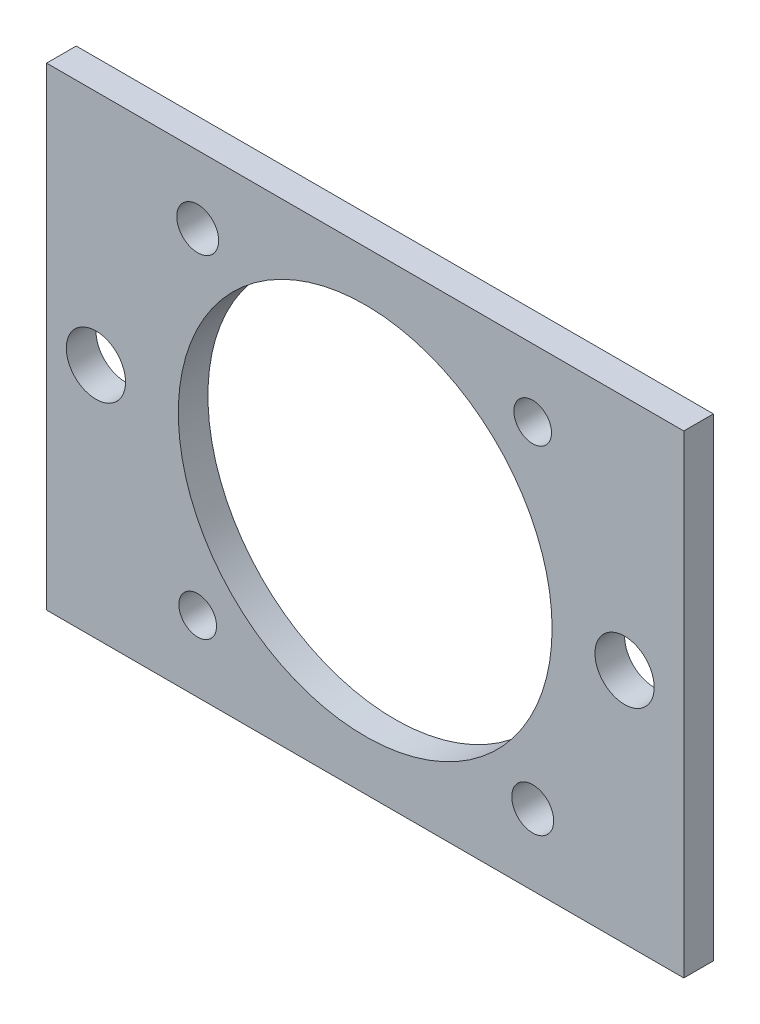
SolidWorks part; units mm, degrees
ref_plane "Front Plane" through (0, 0, 0) normal (0, 0, 1) x (1, 0, 0)
ref_plane "Top Plane" through (0, 0, 0) normal (0, 1, 0) x (1, 0, 0)
ref_plane "Right Plane" through (0, 0, 0) normal (1, 0, 0) x (0, 0, -1)
sketch "Sketch2" plane through (0, 0, 0) normal (0, 0, 1) x (1, 0, 0)
  line L0 (-34.163, -3.5154) -> (-28.8748, 0) construction
  line L1 (-34.163, -25.4) -> (34.163, -25.4)
  line L2 (-34.163, -25.4) -> (-34.163, 25.4)
  line L3 (-34.163, 25.4) -> (34.163, 25.4)
  line L4 (34.163, -25.4) -> (34.163, 25.4)
  line L5 (-28.8748, 0) -> (0, 0) construction
  line L6 (0, 0) -> (27.813, 0) construction
  line L7 (-17.9605, -17.7878) -> (17.9605, -17.7878) construction
  line L8 (-17.9605, -17.7878) -> (-17.9605, 18.1332) construction
  line L9 (-17.9605, 18.1332) -> (17.9605, 18.1332) construction
  line L10 (17.9605, -17.7878) -> (17.9605, 18.1332) construction
  line L11 (-17.9605, -17.7878) -> (17.9605, 18.1332) construction
  line L12 (-17.9605, 18.1332) -> (17.9605, -17.7878) construction
  line L13 (27.813, 0) -> (34.163, 0) construction
  circle A0 centre (-17.9605, 18.1332) radius 2.2479
  circle A1 centre (17.9605, 18.1332) radius 2.0193
  circle A2 centre (17.9605, -17.7878) radius 2.2479
  circle A3 centre (-17.9605, -17.7878) radius 2.0193
  circle A4 centre (0, 0) radius 20.0406
  circle A5 centre (-28.8748, 0) radius 3.175
  circle A6 centre (27.813, 0) radius 3.175
  point P0 (0, 0)
  point P6 (0, 0.1727)
  dimension "D5" = 4.4958
  dimension "D6" = 4.0386
  dimension "D7" = 40.0812
  dimension "D3" = 50.8
  dimension "D8" = 7.6122
  dimension "D12" = 6.35
  dimension "D13" = 6.35
  dimension "D14" = 5.2882
  dimension "D15" = 28.8748
  dimension "D1" = 50.8
  dimension "D2" = 68.326
  dimension "D4" = 35.921
  dimension "D9" = 16.2025
  dimension "D10" = 34.163
  dimension "D11" = 25.4
extrude "Boss-Extrude1" add sketch "Sketch2" along normal blind 3.175
